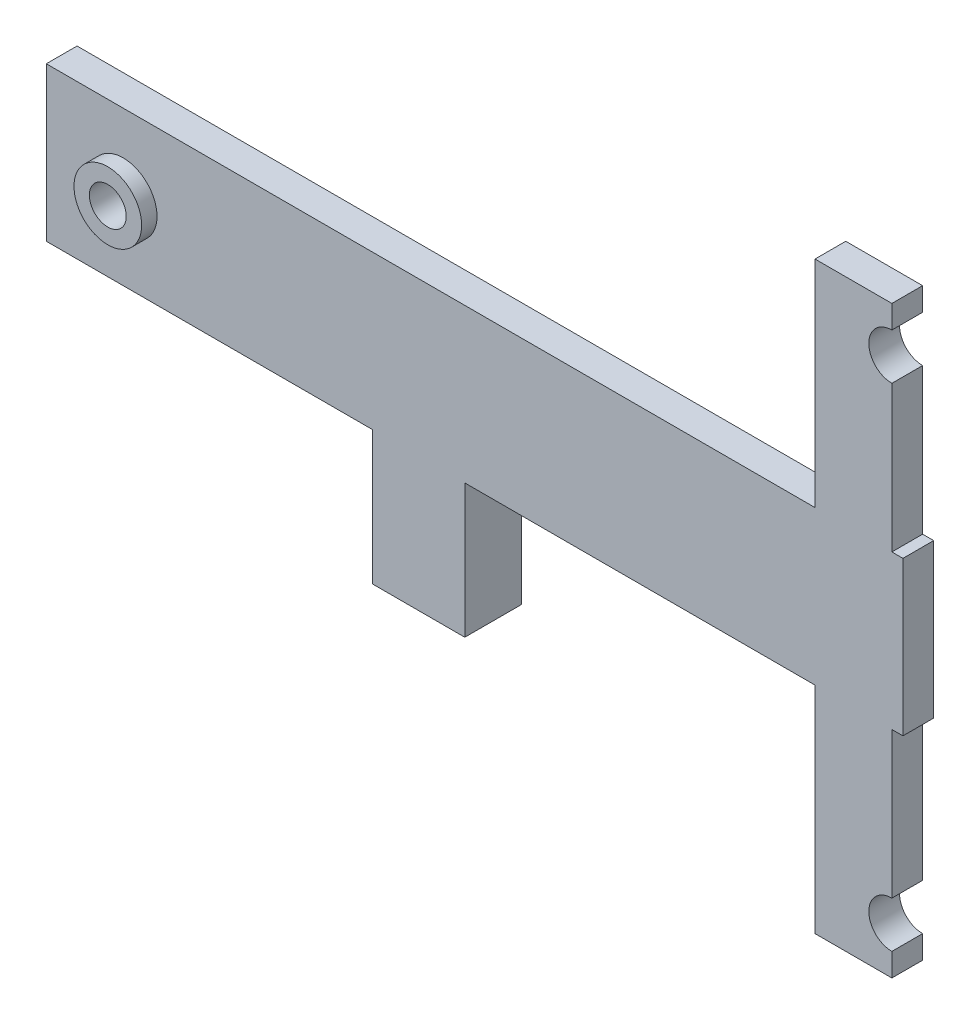
SolidWorks part; units mm, degrees
ref_plane "Front Plane" through (0, 0, 0) normal (0, 0, 1) x (1, 0, 0)
ref_plane "Top Plane" through (0, 0, 0) normal (0, 1, 0) x (1, 0, 0)
ref_plane "Right Plane" through (0, 0, 0) normal (1, 0, 0) x (0, 0, -1)
sketch "Sketch1" plane through (0, 0, 0) normal (0, 0, 1) x (1, 0, 0)
  line L0 (-5, -5) -> (-5, 5)
  line L1 (-5, 5) -> (95, 5)
  line L2 (95, 5) -> (95, -5)
  line L3 (95, -5) -> (-5, -5)
  line L4 (0, 46.8891) -> (0, -81.8139) construction
  line L5 (-56.632, 0) -> (192.6477, 0) construction
  line L10 (45, -5) -> (45, -19)
  line L11 (45, -19) -> (50, -19)
  line L13 (50, -5) -> (45, -5)
  line L14 (50, -19) -> (50, -5)
  line L15 (45, 19) -> (50, 19)
  line L16 (45, 5) -> (45, 19)
  line L17 (50, 5) -> (45, 5)
  line L18 (50, 19) -> (50, 5)
  line L19 (0, 0) -> (5, 0)
  line L20 (5, 0) -> (50.72, 0)
  line L21 (5, 0) -> (16.43, 0)
  line L22 (16.43, 0) -> (19.22, 0)
  line L23 (19.22, 0) -> (19.22, -2.25)
  line L24 (19.22, 0) -> (19.22, 1.905)
  line L25 (19.22, 0) -> (19.22, -1.905)
  line L26 (50, -19) -> (47.5, -19)
  line L27 (50.72, 0) -> (50.72, 5)
  line L28 (50.72, 0) -> (50.72, -5)
  circle A0 centre (0, 0) radius 1.2
  arc A1 (50, 14.5) -> (50, 17.5) centre (50, 16) cw
  arc A2 (50, -14.5) -> (50, -17.5) centre (50, -16) ccw
  circle A3 centre (19.22, -2.25) radius 0.254
  point P33 (50, -12)
  dimension "D3" = 5
  dimension "D5" = 2.4
  dimension "D7" = 44.28
  dimension "D6" = 45
  dimension "D1" = 10
  dimension "D2" = 100
  dimension "D4" = 5
extrude "Boss-Extrude1" add sketch "Sketch1" along normal mid plane 2 contours L3 L2 L1 L0 A0 | L18 A1 L15 L16 L1 | A2 L14 L3 L10 L11
sketch "Sketch2" plane through (0, 0, 0) normal (0, 0, 1) x (1, 0, 0)
  circle A0 centre (0, 0) radius 2.2
  circle A1 centre (0, 0) radius 1.2
  dimension "D1" = 2.4
  dimension "D2" = 4.4
extrude "Boss-Extrude2" add sketch "Sketch2" along normal mid plane 4
sketch "Sketch3" plane through (0, 0, -1) normal (0, 0, -1) x (-1, 0, 0)
  line L1 (-19.22, -1.696) -> (-22.22, -1.696)
  line L3 (-19.22, -1.696) -> (-16.22, -1.696)
  line L4 (-16.22, -1.696) -> (-16.22, -9.062)
  line L8 (-16.22, -11.696) -> (-16.22, -9.062)
  line L11 (-16.22, -12.696) -> (-16.22, -11.696)
  line L12 (-22.22, -1.696) -> (-22.22, -13.696)
  line L13 (-22.22, -13.696) -> (-16.22, -13.696)
  line L14 (-16.22, -13.696) -> (-16.22, -12.696)
extrude "Boss-Extrude3" add sketch "Sketch3" along normal blind 1.7018 and the other way blind 2 contours L3 L4 L8 L11 L14 L13 L12 L1
sketch "Sketch5" plane through (0, 0, -2.7018) normal (0, 0, -1) x (-1, 0, 0)
  line L0 (-16.22, -1.696) -> (-22.22, -1.696) construction
  line L2 (-16.22, -1.696) -> (-16.22, -13.696) construction
  circle A0 centre (-19.22, -4.696) radius 1
  dimension "D1" = 3
  dimension "D2" = 3
extrude "Cut-Extrude3" cut sketch "Sketch5" against normal blind 2 contours A0
